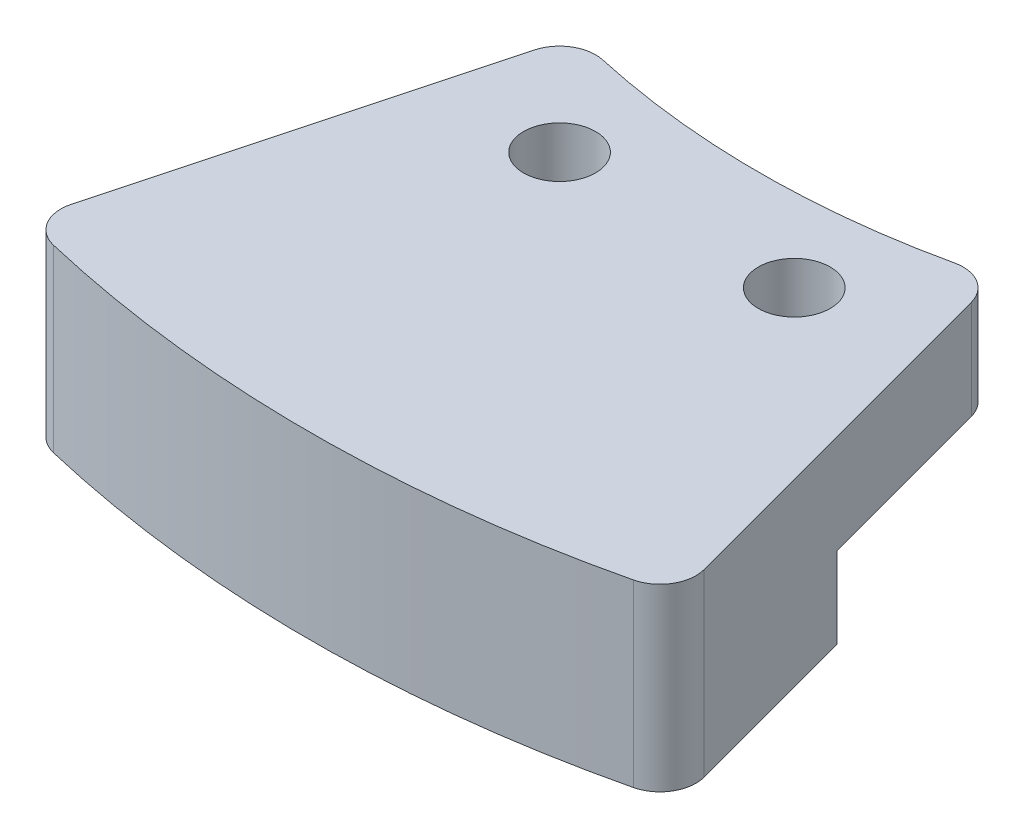
SolidWorks part; units mm, degrees
material "5052-H34"
ref_plane "正面" through (0, 0, 0) normal (0, 0, 1) x (1, 0, 0)
ref_plane "平面" through (0, 0, 0) normal (0, 1, 0) x (1, 0, 0)
ref_plane "右側面" through (0, 0, 0) normal (1, 0, 0) x (0, 0, -1)
sketch "ｽｹｯﾁ1" plane through (0, 0, 0) normal (0, 1, 0) x (1, 0, 0)
  line L0 (0, 0) -> (0, -54) construction
  line L1 (0, 0) -> (-6.5263, -49.5722) construction
  line L2 (-11.6469, -43.4667) -> (-18.1173, -67.6148)
  line L3 (11.6469, -43.4667) -> (18.1173, -67.6148)
  line L4 (0, 0) -> (-11.6469, -43.4667) construction
  line L5 (0, 0) -> (11.6469, -43.4667) construction
  circle A0 centre (0, 0) radius 54 construction
  circle A1 centre (0, 0) radius 50 construction
  circle A2 centre (-6.5263, -49.5722) radius 2
  circle A3 centre (6.5263, -49.5722) radius 2
  arc A4 (-18.1173, -67.6148) -> (18.1173, -67.6148) centre (0, 0) ccw
  arc A5 (-11.6469, -43.4667) -> (11.6469, -43.4667) centre (0, 0) ccw
  arc A6 (11.6469, -43.4667) -> (-11.6469, -43.4667) centre (0, 0) ccw construction
  arc A7 (18.1173, -67.6148) -> (-18.1173, -67.6148) centre (0, 0) ccw construction
  dimension "D1" = 108
  dimension "D2" = 100
  dimension "D3" = 4
  dimension "D4" = 7.5
  dimension "D6" = 140
  dimension "D7" = 5
  dimension "D5" = 30
extrude "ﾎﾞｽ - 押し出し1" add sketch "ｽｹｯﾁ1" along normal blind 10
sketch "ｽｹｯﾁ2" plane through (0, 0, 0) normal (0, -1, 0) x (1, 0, 0)
  line L0 (18.1173, 67.6148) -> (11.6469, 43.4667) construction
  line L1 (-11.6469, 43.4667) -> (-18.1173, 67.6148) construction
  line L2 (14.8821, 55.5407) -> (11.6469, 43.4667)
  line L3 (-11.6469, 43.4667) -> (-14.8821, 55.5407)
  line L4 (-14.8821, 55.5407) -> (-18.1173, 67.6148) construction
  line L5 (18.1173, 67.6148) -> (14.8821, 55.5407) construction
  arc A0 (14.8821, 55.5407) -> (-14.8821, 55.5407) centre (0, 0) ccw
  arc A1 (11.6469, 43.4667) -> (-11.6469, 43.4667) centre (0, 0) ccw construction
  arc A2 (11.6469, 43.4667) -> (-11.6469, 43.4667) centre (0, 0) ccw
  arc A3 (-14.8821, 55.5407) -> (14.8821, 55.5407) centre (0, 0) ccw construction
  dimension "D1" = 115
extrude "ｶｯﾄ - 押し出し1" cut sketch "ｽｹｯﾁ2" against normal blind 4.5
fillet "ﾌｨﾚｯﾄ1" radius 2 4 edges at (-11.6469, 7.25, 43.4667) (11.6469, 7.25, 43.4667) (18.1173, 5, 67.6148) (-18.1173, 5, 67.6148)
